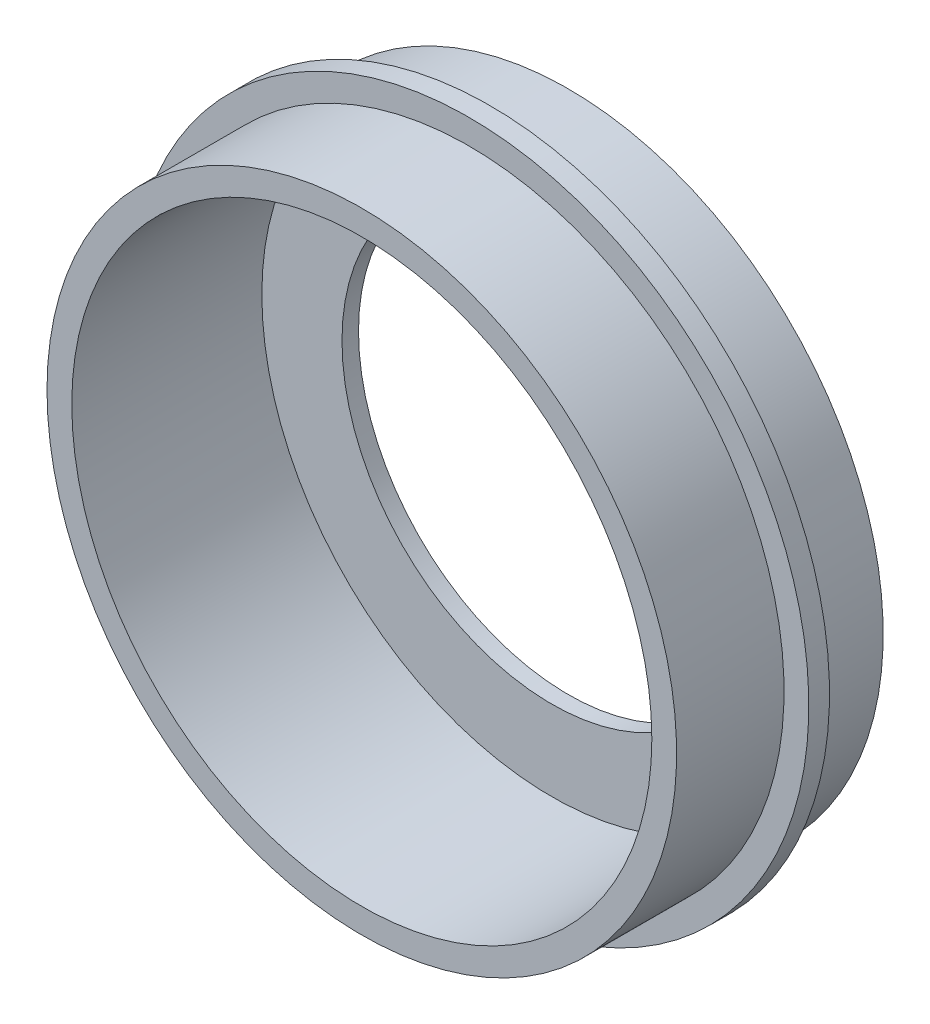
SolidWorks part; units mm, degrees
ref_plane "Front Plane" through (0, 0, 0) normal (0, 0, 1) x (1, 0, 0)
ref_plane "Top Plane" through (0, 0, 0) normal (0, 1, 0) x (1, 0, 0)
ref_plane "Right Plane" through (0, 0, 0) normal (1, 0, 0) x (0, 0, -1)
sketch "Sketch6" plane through (0, 0, 0) normal (1, 0, 0) x (0, 0, -1)
  line L0 (0, 0) -> (-40.103, 0) construction
  line L1 (0, 0) -> (0, 25.4) construction
  line L2 (0, 25.4) -> (-2, 25.4)
  line L3 (-2, 25.4) -> (-2, 35.1)
  line L4 (-2, 35.1) -> (-25, 35.1)
  line L5 (-25, 35.1) -> (-25, 38.1)
  line L6 (-25, 38.1) -> (-12, 38.1)
  line L7 (-12, 38.1) -> (-12, 41.1)
  line L8 (-12, 41.1) -> (-9.5, 41.1)
  line L9 (-9.5, 41.1) -> (-9.5, 38.1)
  line L10 (-9.5, 38.1) -> (0, 38.1)
  line L11 (0, 38.1) -> (0, 25.4)
  dimension "D2" = 25.4
  dimension "D3" = 25
  dimension "D4" = 23
  dimension "D5" = 3
  dimension "D6" = 3
  dimension "D7" = 2.5
  dimension "D8" = 13
  dimension "D9" = 38.1
revolve "Revolve1" add sketch "Sketch6" angle 360 about L0
